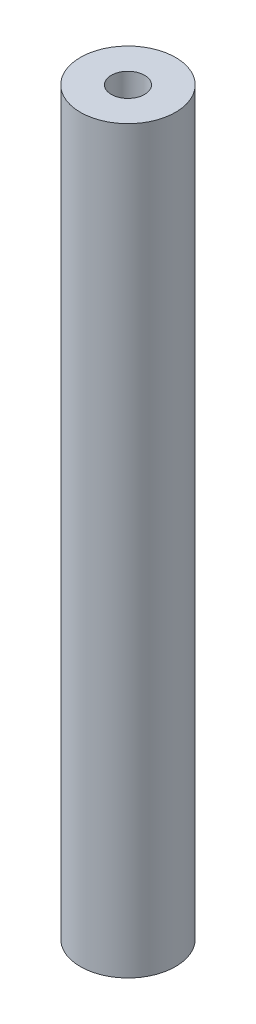
SolidWorks part; units mm, degrees
ref_plane "Front Plane" through (0, 0, 0) normal (0, 0, 1) x (1, 0, 0)
ref_plane "Top Plane" through (0, 0, 0) normal (0, 1, 0) x (1, 0, 0)
ref_plane "Right Plane" through (0, 0, 0) normal (1, 0, 0) x (0, 0, -1)
sketch "Sketch1" plane through (0, 0, 0) normal (0, 1, 0) x (1, 0, 0)
  circle A0 centre (0, 0) radius 1.4
  circle A1 centre (0, 0) radius 4
  dimension "D1" = 8
  dimension "D2" = 2.8
extrude "Boss-Extrude1" add sketch "Sketch1" along normal blind 62.2
